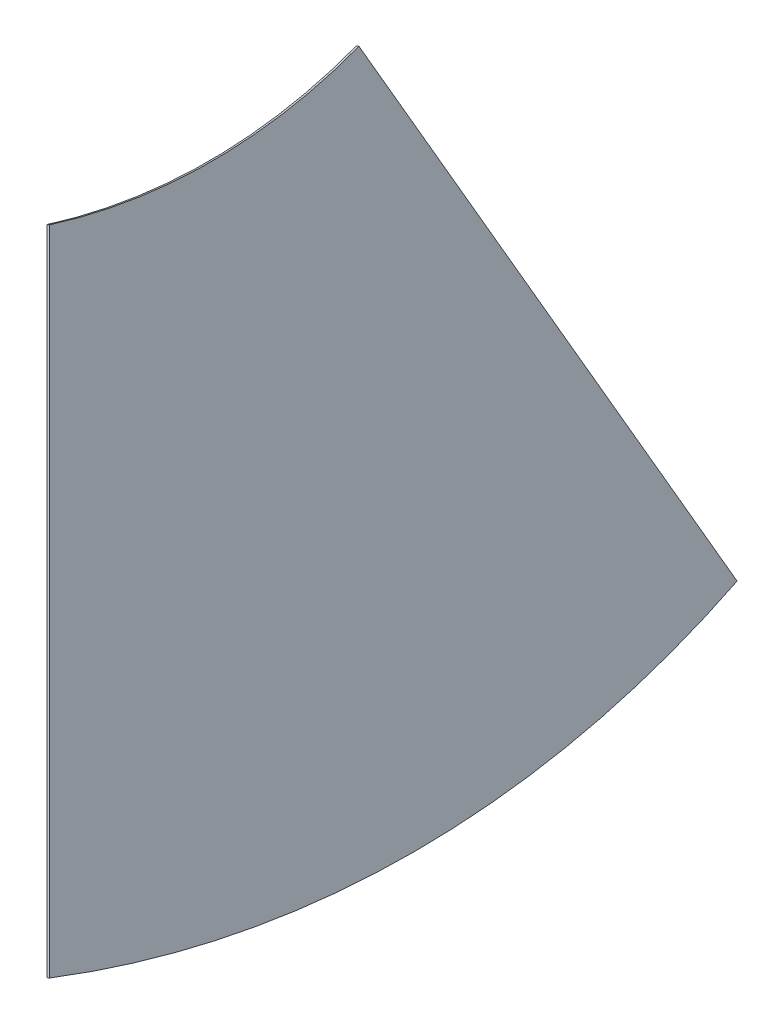
SolidWorks part; units mm, degrees
ref_plane "Front Plane" through (0, 0, 0) normal (0, 0, 1) x (1, 0, 0)
ref_plane "Top Plane" through (0, 0, 0) normal (0, 1, 0) x (1, 0, 0)
ref_plane "Right Plane" through (0, 0, 0) normal (1, 0, 0) x (0, 0, -1)
sketch "Sketch2" plane through (27.418, 53.2205, 84.5047) normal (-0.9258, -0.378, 0) x (-0.268, 0.6564, 0.7052)
  line L19 (-183.0128, 30.9603) -> (-392.8945, -63.1125)
  line L20 (-184.3911, -272.728) -> (-89.2032, -63.3498)
  line L21 (-392.8945, -63.1125) -> (-394.1931, -60.2152)
  line L25 (-394.1931, -60.2152) -> (-120.4344, 62.4884)
  line L26 (-60.2329, 0.374) -> (-57.3426, -0.94)
  line L28 (-120.4344, 62.4884) -> (-119.1358, 59.5911)
  line L29 (-120.4344, 62.4884) -> (-119.1358, 59.5911)
  line L30 (-119.1358, 59.5911) -> (-392.8945, -63.1125)
  line L31 (-119.1358, 59.5911) -> (-392.8945, -63.1125) construction
  line L32 (-181.5008, -274.042) -> (-184.3911, -272.728)
  line L34 (-184.3911, -272.728) -> (-60.2329, 0.374)
  line L35 (-184.3911, -272.728) -> (-60.2329, 0.374) construction
  line L36 (-60.2329, 0.374) -> (-57.3426, -0.94)
  line L37 (-60.2329, 0.374) -> (-57.3426, -0.94)
  line L38 (-57.3426, -0.94) -> (-181.5008, -274.042)
  line L39 (-60.2329, 0.374) -> (-184.3911, -272.728) construction
  arc A0 (-184.3911, -272.728) -> (-392.8945, -63.1125) centre (24.7046, 143.7646) cw
  arc A2 (-183.0128, 30.9603) -> (-89.2032, -63.3498) centre (43.0974, 162.0598) ccw
  dimension "D1" = 230
extrude "Boss-Extrude1" add sketch "Sketch2" along normal mid plane 1.27 contours L19 A2 L20 A0
